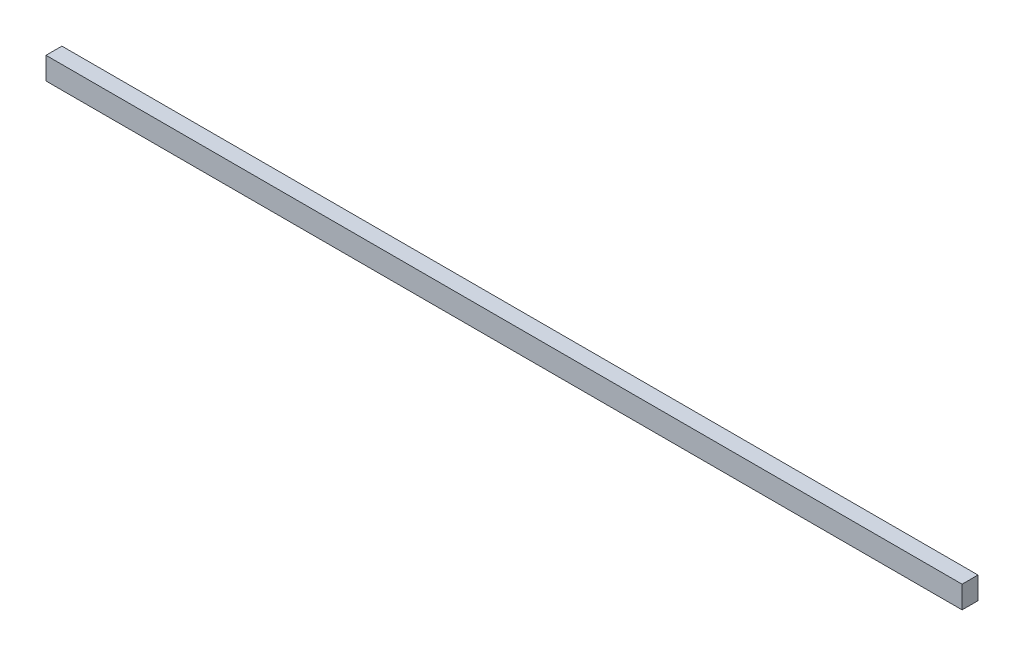
SolidWorks part; units mm, degrees
ref_plane "Front Plane" through (0, 0, 0) normal (0, 0, 1) x (1, 0, 0)
ref_plane "Top Plane" through (0, 0, 0) normal (0, 1, 0) x (1, 0, 0)
ref_plane "Right Plane" through (0, 0, 0) normal (1, 0, 0) x (0, 0, -1)
sketch "Sketch1" plane through (0, 0, 0) normal (0, 0, 1) x (1, 0, 0)
  line L0 (-18.1325, 3.5) -> (-18.1325, 3) construction
  line L1 (-305.9848, -3.5) -> (-18.1325, -3.5)
  line L2 (-305.9848, -3.5) -> (-305.9848, 3.5)
  line L3 (-305.9848, 3.5) -> (-18.1325, 3.5)
  line L4 (-18.1325, -3.5) -> (-18.1325, 3.5)
  point P4 (0, 0)
  point P5 (-18.4989, 3.5492)
  point P6 (-18.5298, 2.4731)
  point P7 (-18.1325, 5.5004)
extrude "Boss-Extrude1" add sketch "Sketch1" along normal blind 5
